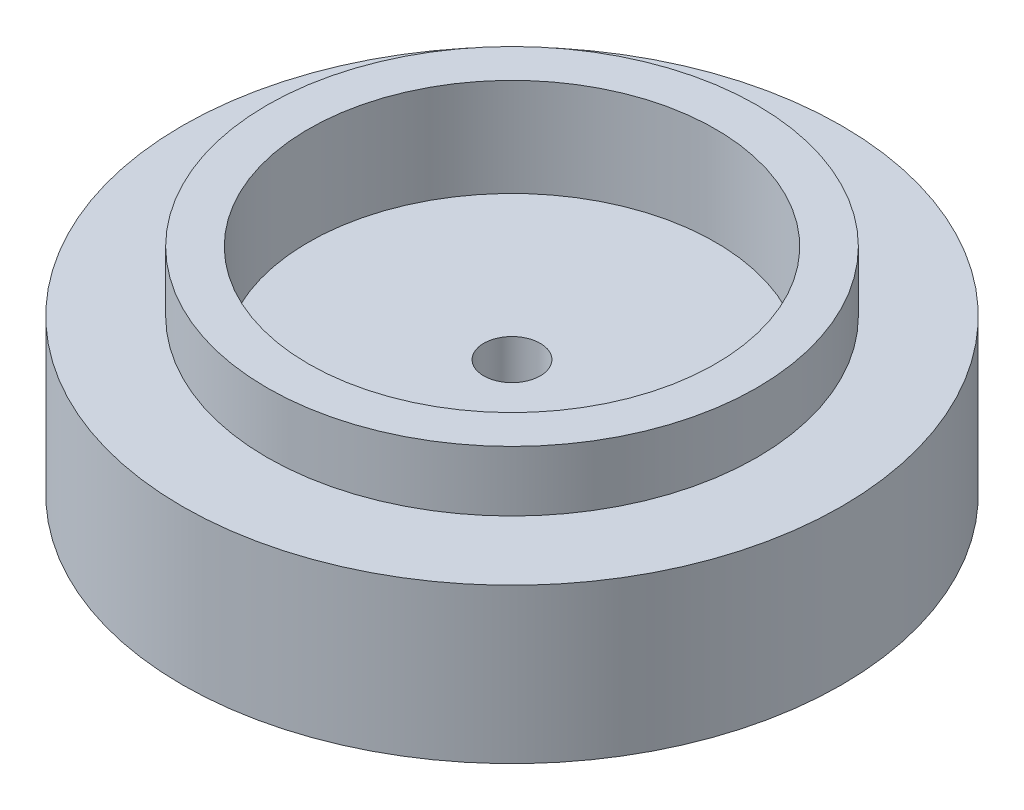
SolidWorks part; units mm, degrees
material "ABS"
ref_plane "Front" through (0, 0, 0) normal (0, 0, 1) x (1, 0, 0)
ref_plane "Top" through (0, 0, 0) normal (0, 1, 0) x (1, 0, 0)
ref_plane "Right" through (0, 0, 0) normal (1, 0, 0) x (0, 0, -1)
sketch "Sketch1" plane through (0, 0, 0) normal (0, 1, 0) x (1, 0, 0)
  circle A0 centre (0, 0) radius 17.5
  dimension "D1" = 35
extrude "Boss-Extrude1" add sketch "Sketch1" along normal blind 8.2
sketch "Sketch3" plane through (0, 8.2, 0) normal (0, 1, 0) x (1, 0, 0)
  circle A0 centre (0, 0) radius 13
  dimension "D1" = 26
sketch "Sketch6" plane through (0, 0, 0) normal (0, -1, 0) x (1, 0, 0)
  circle A0 centre (0, 0) radius 12
  dimension "D1" = 24
extrude "Boss-Extrude4" add sketch "Sketch6" along normal blind 2
extrude "Boss-Extrude5" add sketch "Sketch3" along normal blind 3.2
sketch "Sketch7" plane through (0, -2, 0) normal (0, -1, 0) x (1, 0, 0)
  circle A0 centre (0, 0) radius 10.8
  dimension "D1" = 21.6
extrude "Cut-Extrude3" cut sketch "Sketch7" against normal blind 4
sketch "Sketch8" plane through (0, 11.4, 0) normal (0, 1, 0) x (1, 0, 0)
  circle A0 centre (0, 0) radius 10.8
  dimension "D1" = 21.6
extrude "Cut-Extrude4" cut sketch "Sketch8" against normal blind 5.2
sketch "Sketch9" plane through (0, 6.2, 0) normal (0, 1, 0) x (1, 0, 0)
  circle A0 centre (0, 0) radius 1.5
  dimension "D1" = 3
extrude "Cut-Extrude5" cut sketch "Sketch9" against normal through all
